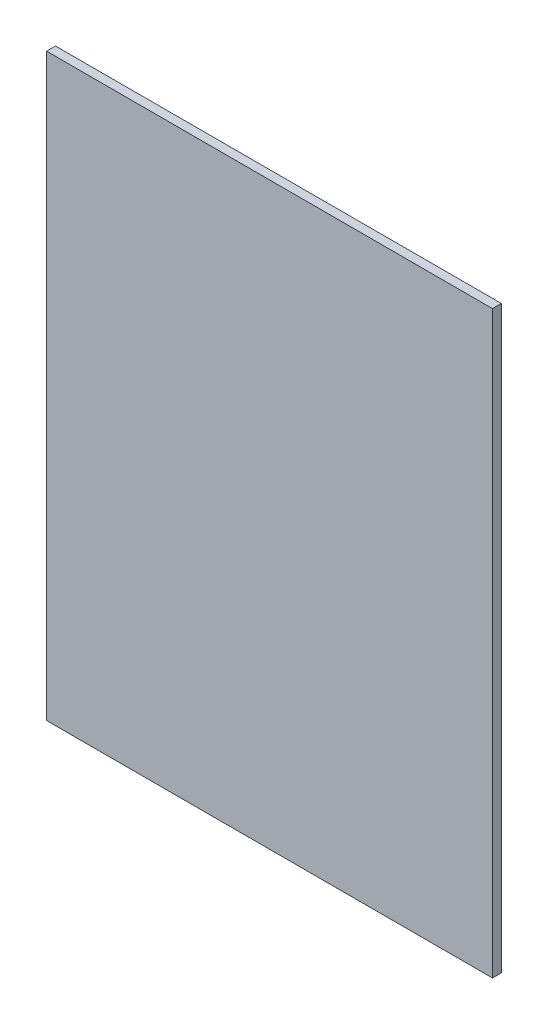
SolidWorks part; units mm, degrees
material "AISI 316 Stainless Steel Sheet (SS)"
ref_plane "Front" through (0, 0, 0) normal (0, 0, 1) x (1, 0, 0)
ref_plane "Top" through (0, 0, 0) normal (0, 1, 0) x (1, 0, 0)
ref_plane "Right" through (0, 0, 0) normal (1, 0, 0) x (0, 0, -1)
sketch "Sketch1" plane through (0, 0, 0) normal (0, 0, 1) x (1, 0, 0)
  line L1 (-50, -65) -> (50, -65)
  line L2 (-50, -65) -> (-50, 65)
  line L3 (-50, 65) -> (50, 65)
  line L4 (50, -65) -> (50, 65)
  line L5 (-50, -65) -> (50, 65) construction
  line L6 (-50, 65) -> (50, -65) construction
  point P0 (0, 0)
  dimension "D1" = 100
  dimension "D2" = 130
extrude "Boss-Extrude1" add sketch "Sketch1" along normal mid plane 2
